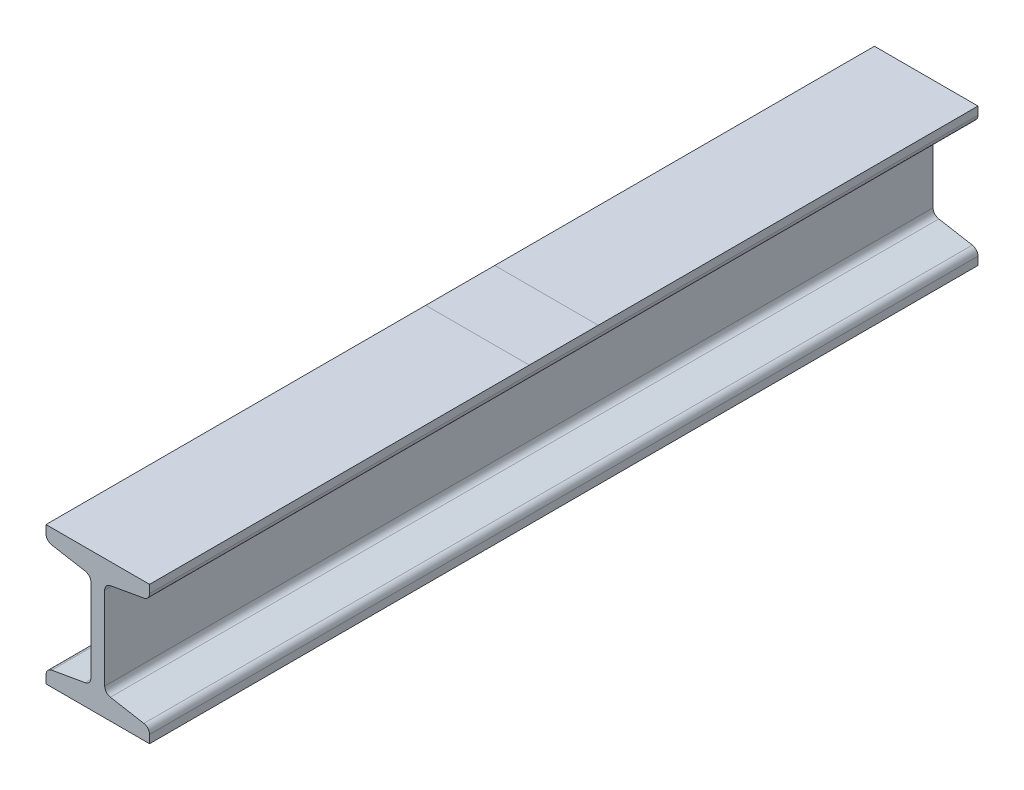
SolidWorks part; units mm, degrees
ref_plane "Front Plane" through (0, 0, 0) normal (0, 0, 1) x (1, 0, 0)
ref_plane "Top Plane" through (0, 0, 0) normal (0, 1, 0) x (1, 0, 0)
ref_plane "Right Plane" through (0, 0, 0) normal (1, 0, 0) x (0, 0, -1)
sketch "Sketch1" plane through (0, 0, 0) normal (0, 0, 1) x (1, 0, 0)
  line L0 (0, 75.4455) -> (0, -52.0857) construction
  line L12 (-37.5, 50) -> (37.5, 50)
  line L17 (-5, -34.2694) -> (-5, 34.2694)
  line L19 (5, -34.2694) -> (5, 34.2694)
  line L20 (-32.6398, 0) -> (37.5, 0) construction
  line L21 (37.5, -50) -> (37.5, -40)
  line L22 (37.5, 50) -> (37.5, 40)
  line L23 (37.5, 40) -> (5, 34.2694)
  line L24 (-37.5, 50) -> (-37.5, 40)
  line L25 (-37.5, 40) -> (-5, 34.2694)
  line L26 (37.5, -40) -> (5, -34.2694)
  line L27 (-37.5, -50) -> (37.5, -50)
  line L28 (-37.5, -50) -> (-37.5, -40)
  line L29 (-37.5, -40) -> (-5, -34.2694)
  point P3 (0, 0)
  point P11 (0, 50)
  point P21 (0, 0)
  dimension "D1" = 10
  dimension "D2" = 100
  dimension "D3" = 100
  dimension "D4" = 75
  dimension "D5" = 10
  dimension "D6" = 100
extrude "Boss-Extrude1" add sketch "Sketch1" along normal blind 600
sketch "Sketch2" plane through (0, 50, 0) normal (0, 1, 0) x (1, 0, 0)
  line L0 (37.5, -600) -> (37.5, 0) construction
  line L1 (-37.5, -325) -> (37.5, -325)
  line L2 (-37.5, -325) -> (-37.5, -275)
  line L3 (-37.5, -275) -> (37.5, -275)
  line L4 (37.5, -325) -> (37.5, -275)
  line L5 (-37.5, -325) -> (37.5, -275) construction
  line L6 (-37.5, -275) -> (37.5, -325) construction
  point P0 (0, -300)
  dimension "D1" = 300
  dimension "D2" = 50
  dimension "D3" = 75
split line "Split Line1"
sketch "Sketch3" plane through (0, -50, 0) normal (0, -1, 0) x (1, 0, 0)
  line L0 (37.5, 600) -> (37.5, 0) construction
  line L1 (-37.5, 600) -> (37.5, 600)
  line L2 (-37.5, 600) -> (-37.5, 560)
  line L3 (-37.5, 560) -> (37.5, 560)
  line L4 (37.5, 600) -> (37.5, 560)
  line L5 (-37.5, 600) -> (-37.5, 0) construction
  line L6 (37.5, 0) -> (-37.5, 0)
  line L7 (37.5, 0) -> (37.5, 40)
  line L8 (37.5, 40) -> (-37.5, 40)
  line L9 (-37.5, 0) -> (-37.5, 40)
  dimension "D1" = 40
  dimension "D2" = 40
split line "Split Line2"
fillet "Fillet1" radius 5 8 edges at (37.5, -40, 300) (37.5, 40, 300) (-37.5, 40, 300) (-37.5, -40, 300) (5, -34.2694, 300) (-5, -34.2694, 300) (5, 34.2694, 300) (-5, 34.2694, 300)
